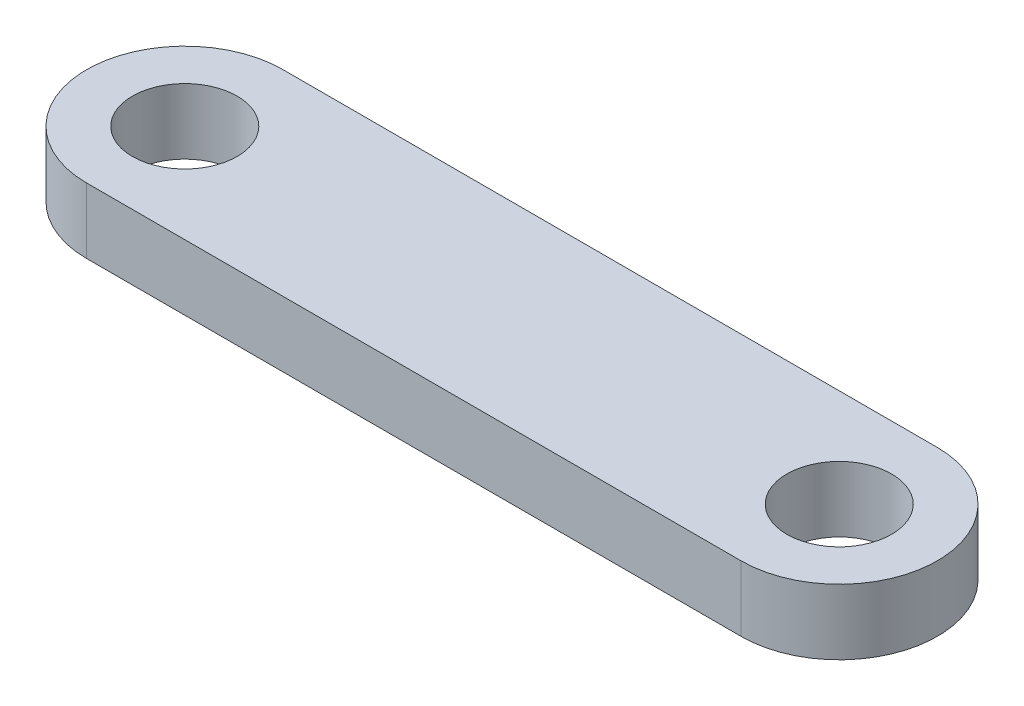
SolidWorks part; units mm, degrees
ref_plane "Front Plane" through (0, 0, 0) normal (0, 0, 1) x (1, 0, 0)
ref_plane "Top Plane" through (0, 0, 0) normal (0, 1, 0) x (1, 0, 0)
ref_plane "Right Plane" through (0, 0, 0) normal (1, 0, 0) x (0, 0, -1)
sketch "Sketch1" plane through (0, 0, 0) normal (0, 1, 0) x (1, 0, 0)
  line L0 (0, 7.5) -> (50, 7.5)
  line L1 (50, -7.5) -> (0, -7.5)
  arc A0 (0, 7.5) -> (0, -7.5) centre (0, 0) ccw
  arc A1 (50, -7.5) -> (50, 7.5) centre (50, 0) ccw
  circle A2 centre (0, 0) radius 4
  circle A3 centre (50, 0) radius 4
  dimension "D1" = 15
  dimension "D2" = 15
  dimension "D4" = 8
  dimension "D5" = 8
  dimension "D3" = 50
extrude "Boss-Extrude1" add sketch "Sketch1" along normal blind 5
scale "Scale1" scale about centroid uniform scaling yes scale factor 0.7
